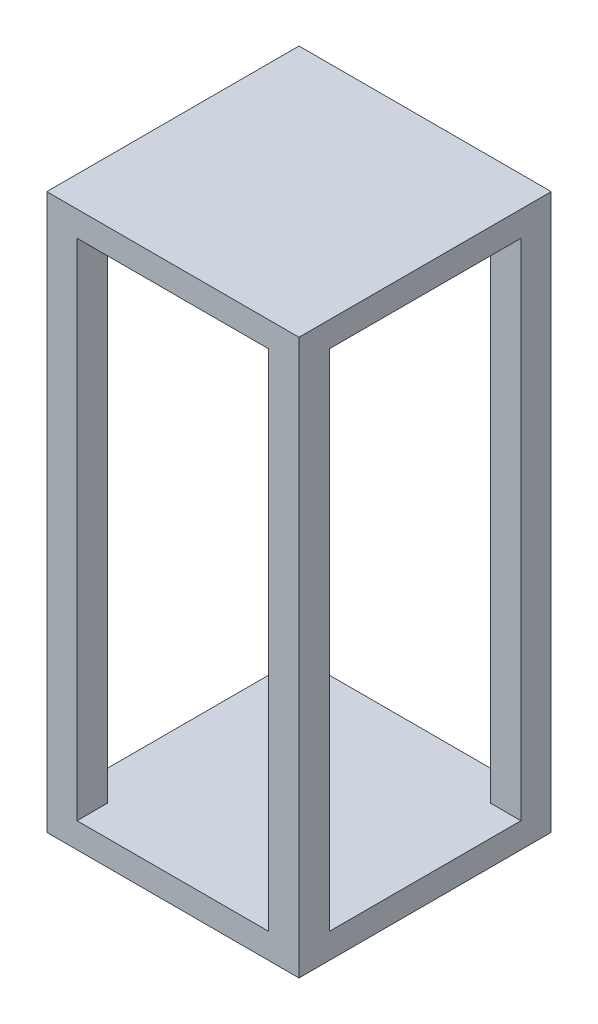
SolidWorks part; units mm, degrees
ref_plane "Piano frontale" through (0, 0, 0) normal (0, 0, 1) x (1, 0, 0)
ref_plane "Piano superiore" through (0, 0, 0) normal (0, 1, 0) x (1, 0, 0)
ref_plane "Piano destro" through (0, 0, 0) normal (1, 0, 0) x (0, 0, -1)
sketch "Schizzo1" plane through (0, 0, 0) normal (0, 1, 0) x (1, 0, 0)
  line L1 (-25, -25) -> (25, -25)
  line L2 (-25, -25) -> (-25, 25)
  line L3 (-25, 25) -> (25, 25)
  line L4 (25, -25) -> (25, 25)
  line L5 (-25, -25) -> (25, 25) construction
  line L6 (-25, 25) -> (25, -25) construction
  point P0 (0, 0)
  dimension "D1" = 50
  dimension "D2" = 50
extrude "Estrusione-Estrusione1" add sketch "Schizzo1" along normal blind 5
sketch "Schizzo2" plane through (0, 5, 0) normal (0, 1, 0) x (1, 0, 0)
  line L0 (25, 25) -> (19, 25)
  line L1 (-25, 25) -> (-19, 25)
  line L2 (-25, 25) -> (-25, 19)
  line L3 (-25, 19) -> (-19, 19)
  line L4 (-19, 25) -> (-19, 19)
  line L5 (25, 25) -> (25, 19)
  line L6 (25, 19) -> (19, 19)
  line L7 (19, 25) -> (19, 19)
  line L8 (25, -25) -> (25, -19)
  line L9 (25, -25) -> (19, -25)
  line L10 (19, -25) -> (19, -19)
  line L11 (25, -19) -> (19, -19)
  line L12 (-25, -25) -> (-19, -25)
  line L13 (-25, -25) -> (-25, -19)
  line L14 (-25, -19) -> (-19, -19)
  line L15 (-19, -25) -> (-19, -19)
  point P20 (-2.5, 0)
  point P21 (0, 0)
  dimension "D1" = 6
  dimension "D2" = 6
  dimension "D3" = 4
extrude "Estrusione-Estrusione2" add sketch "Schizzo2" along normal blind 100
sketch "Schizzo3" plane through (0, 105, 0) normal (0, 1, 0) x (1, 0, 0)
  line L1 (-25, 25) -> (25, 25)
  line L2 (-25, 25) -> (-25, -25)
  line L3 (-25, -25) -> (25, -25)
  line L4 (25, 25) -> (25, -25)
extrude "Estrusione-Estrusione3" add sketch "Schizzo3" along normal blind 5
sketch "Schizzo4" plane through (0, 0, 0) normal (0, 0, 1) x (1, 0, 0)
  line L0 (0, 80.4646) -> (0, -24.9369) construction
  circle A0 centre (0, 101.5014) radius 5
  circle A1 centre (0, 101.5014) radius 3
  dimension "D1" = 10
extrude "Estrusione-Estrusione4" add sketch "Schizzo4" along normal mid plane 2.5 separate body
fillet "Raccordo1" radius 0.9 4 edges at (3, 101.5014, -1.25) (5, 101.5014, -1.25) (3, 101.5014, 1.25) (5, 101.5014, 1.25)
